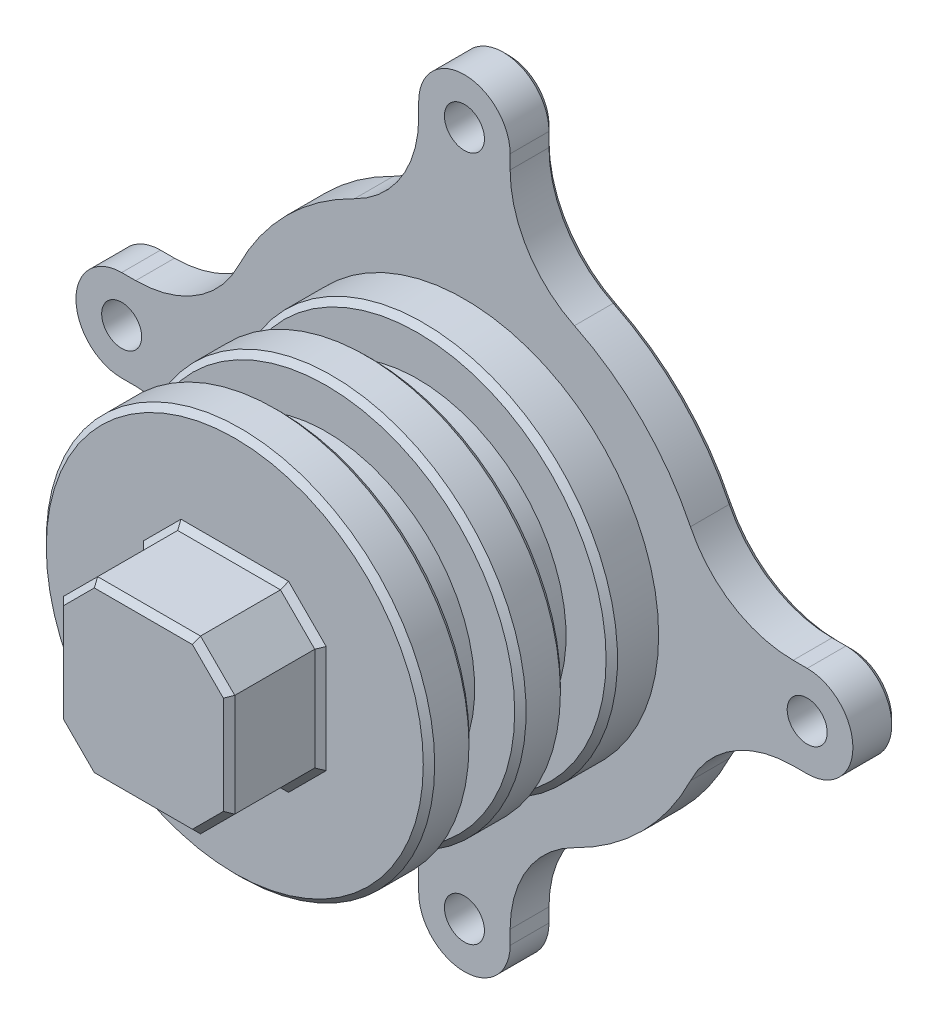
SolidWorks part; units mm, degrees
ref_plane "Front Plane" through (0, 0, 0) normal (0, 0, 1) x (1, 0, 0)
ref_plane "Top Plane" through (0, 0, 0) normal (0, 1, 0) x (1, 0, 0)
ref_plane "Right Plane" through (0, 0, 0) normal (1, 0, 0) x (0, 0, -1)
sketch "Sketch1" plane through (0, 0, 0) normal (0, 0, 1) x (1, 0, 0)
  circle A0 centre (0, 0) radius 25
  dimension "D1" = 50
ref_plane "Plane1" through (0, 0, 20) normal (0, 0, 1) x (1, 0, 0)
sketch "Sketch2" plane through (0, 0, 20) normal (0, 0, 1) x (1, 0, 0)
  circle A0 centre (0, 0) radius 15
  dimension "D1" = 30
loft "Loft1" add profiles "Sketch2", "Sketch1"
sketch "Sketch3" plane through (0, 0, 20) normal (0, 0, 1) x (1, 0, 0)
  circle A0 centre (0, 0) radius 15
  circle A1 centre (0, 0) radius 15 construction
extrude "Boss-Extrude1" add sketch "Sketch3" along normal blind 5
fillet "Fillet1" radius 10 1 edges at (15, 0, 20)
sketch "Sketch4" plane through (0, 0, 0) normal (0, 0, -1) x (-1, 0, 0)
  line L0 (0, 20) -> (0, -20) construction
  line L1 (-20, 0) -> (20, 0) construction
  circle A0 centre (0, 0) radius 20 construction
  circle A1 centre (0, 20) radius 1.75
  circle A2 centre (-20, 0) radius 1.75
  circle A3 centre (0, -20) radius 1.75
  circle A4 centre (20, 0) radius 1.75
  dimension "D1" = 40
  dimension "D2" = 3.5
  dimension "D3" = 3.5
  dimension "D4" = 3.5
  dimension "D5" = 3.5
extrude "Cut-Extrude1" cut sketch "Sketch4" against normal blind 130
ref_plane "Plane2" through (0, 0, 3) normal (0, 0, -1) x (-1, 0, 0)
sketch "Sketch5" plane through (0, 0, 3) normal (0, 0, -1) x (-1, 0, 0)
  circle A0 centre (0, 20) radius 4
  circle A1 centre (20, 0) radius 4
  circle A3 centre (-20, 0) radius 4
  circle A5 centre (0, -20) radius 4
  dimension "D1" = 8
  dimension "D2" = 8
  dimension "D3" = 8
  dimension "D4" = 8
extrude "Cut-Extrude2" cut sketch "Sketch5" against normal blind 130
sketch "Sketch6" plane through (0, 0, 25) normal (0, 0, 1) x (1, 0, 0)
  circle A0 centre (0, 0) radius 22
  dimension "D1" = 44
extrude "Boss-Extrude2" add sketch "Sketch6" along normal blind 4
sketch "Sketch7" plane through (0, 0, 29) normal (0, 0, 1) x (1, 0, 0)
  circle A0 centre (0, 0) radius 17
  circle A1 centre (0, 0) radius 22 construction
  dimension "D1" = 5
extrude "Boss-Extrude3" add sketch "Sketch7" along normal blind 20
sketch "Sketch8" [suppressed] plane through (0, 0, 0) normal (0, 1, 0) x (1, 0, 0)
  line L0 (0, -48) -> (0, -27)
  line L1 (-17, -48) -> (17, -48) construction
  line L3 (17, -48) -> (17, -28) construction
  line L4 (3, -24) -> (45.4819, -24)
  arc A0 (0, -27) -> (3, -24) centre (3, -27) cw
  point P9 (0, -24)
  dimension "D2" = 3
  dimension "D1" = 24
  dimension "D3" = 17
ref_plane "Plane5" through (14, 0, 0) normal (1, 0, 0) x (0, 0, -1)
sketch "Sketch14" [suppressed] plane through (14, 0, 0) normal (1, 0, 0) x (0, 0, -1)
  line L0 (-28, 20) -> (-28, -20) construction
  circle A0 centre (-24, 0) radius 4
  dimension "D1" = 8
sketch "Sketch9" [suppressed] plane through (0, 0, 48) normal (0, 0, 1) x (1, 0, 0)
  circle A0 centre (0, 0) radius 2.1
  dimension "D1" = 4.2
ref_plane "Plane4" through (14, 0, 0) normal (1, 0, 0) x (0, 0, -1)
sketch "Sketch10" plane through (0, 0, 49) normal (0, 0, 1) x (1, 0, 0)
  circle A0 centre (0, 0) radius 10
  circle A1 centre (0, 0) radius 17 construction
  dimension "D1" = 7
sketch "Sketch13" [suppressed] plane through (0, 0, 0) normal (0, 1, 0) x (1, 0, 0)
  line L0 (17, -28) -> (17, -48) construction
  line L1 (-20, -28) -> (20, -28) construction
  line L2 (17, -31.3668) -> (17, -44.6332)
  line L3 (0, -28) -> (0, -48) construction
  line L4 (-17, -28) -> (17, -28) construction
  line L5 (-17, -48) -> (17, -48) construction
  arc A0 (17, -31.3668) -> (17, -44.6332) centre (38.5, -38) ccw
  dimension "D1" = 45
  dimension "D2" = 21.5
  dimension "D3" = 10
ref_plane "Plane14" through (0, 0, 39) normal (0, 0, 1) x (1, 0, 0)
sketch "Sketch15" plane through (0, 0, 0) normal (0, 1, 0) x (1, 0, 0)
  line L0 (-17, -29) -> (-17, -49) construction
  line L1 (-21.4316, -33) -> (-13, -33)
  line L2 (-21.4316, -33) -> (-21.4316, -37)
  line L3 (-21.4316, -37) -> (-13, -37)
  line L4 (-13, -33) -> (-13, -37)
  line L5 (-21.5787, -41) -> (-13, -41)
  line L6 (-21.5787, -41) -> (-21.5787, -45)
  line L7 (-21.5787, -45) -> (-13, -45)
  line L8 (-13, -41) -> (-13, -45)
  line L9 (-17, -29) -> (17, -29) construction
  line L10 (0, -29) -> (0, -49) construction
  line L11 (-17, -49) -> (17, -49) construction
  dimension "D1" = 4
  dimension "D2" = 4
  dimension "D3" = 4
  dimension "D4" = 4
  dimension "D5" = 4
  dimension "D6" = 4
revolve "Cut-Revolve1" cut sketch "Sketch15" angle 360 about L10
sketch "Sketch18" plane through (0, 0, 0) normal (0, 0, -1) x (-1, 0, 0)
  circle A0 centre (0, 0) radius 12.5
  dimension "D1" = 25
extrude "Cut-Extrude5" cut sketch "Sketch18" against normal blind 20
sketch "Sketch19" plane through (0, 0, 25) normal (0, 0, -1) x (-1, 0, 0)
  circle A0 centre (0, 0) radius 47.9872
extrude "Cut-Extrude6" cut sketch "Sketch19" along normal through all
sketch "Sketch20" plane through (0, 0, 25) normal (0, 0, -1) x (-1, 0, 0)
  line L0 (-4, 30) -> (-4, 21.6333)
  line L1 (4, 30) -> (4, 21.6333)
  arc A0 (4, 30) -> (-4, 30) centre (0, 30) ccw
  circle A1 centre (0, 30) radius 1.75
  arc A2 (4, 21.6333) -> (-4, 21.6333) centre (0, 0) ccw
  dimension "D1" = 8
  dimension "D2" = 3.5
  dimension "D3" = 44
  dimension "D4" = 30
extrude "Boss-Extrude5" add sketch "Sketch20" against normal blind 4
pattern_circular "CirPattern3" count 4 over 360 about axis through (0, 0, 0) along (0, 0, 1) of "Boss-Extrude5"
fillet "Fillet2" radius 10 8 edges at (21.6333, 4, 27) (21.6333, -4, 27) (4, -21.6333, 27) (-4, -21.6333, 27) (-21.6333, -4, 27) (-21.6333, 4, 27) (-4, 21.6333, 27) (4, 21.6333, 27)
sketch "Sketch21" plane through (0, 0, 29) normal (0, 0, 1) x (1, 0, 0)
  circle A0 centre (0, 0) radius 20
  circle A1 centre (0, 0) radius 17 construction
  circle A2 centre (0, 0) radius 26
  dimension "D1" = 3
  dimension "D2" = 6
chamfer "Chamfer1" distance 0.5 angle 45 5 edges at (-17, 0, 33) (-17, 0, 41) (17, 0, 37) (17, 0, 49) (17, 0, 45)
sketch "Sketch22" plane through (0, 0, 0) normal (0, 1, 0) x (1, 0, 0)
  line L0 (0, -49) -> (0, -60.7563) construction
  line L1 (7.5, -57) -> (-7.5, -57)
  line L2 (7.5, -57) -> (7.5, -49)
  line L3 (7.5, -49) -> (-7.5, -49)
  line L4 (-7.5, -57) -> (-7.5, -49)
  line L5 (-16.5, -49) -> (16.5, -49) construction
  dimension "D1" = 15
  dimension "D2" = 8
  dimension "D3" = 7.5
extrude "Boss-Extrude6" add sketch "Sketch22" along normal mid plane 15
sketch "Sketch23" plane through (0, 0, 0) normal (0, 1, 0) x (1, 0, 0)
  line L0 (0, -57) -> (0, -66) construction
  line L1 (-7.5, -57) -> (7.5, -57) construction
  line L2 (7.5, -57) -> (7.5, -49) construction
  line L3 (7.5, -53.0096) -> (7.5, -49)
  line L4 (-7.5, -49) -> (-7.5, -57) construction
  line L5 (-7.5, -49) -> (-7.5, -53.0096)
  line L6 (-7.5, -49) -> (7.5, -49)
  arc A0 (7.5, -53.0096) -> (-7.5, -53.0096) centre (0, -66) ccw
  dimension "D2" = 30
  dimension "D1" = 9
chamfer "Chamfer2" distance 3 angle 45 4 edges at (7.5, -7.5, 53) (7.5, 7.5, 53) (-7.5, -7.5, 53) (-7.5, 7.5, 53)
chamfer "Chamfer3" distance 0.5 angle 45 16 edges at (-6, -6, 57) (-7.5, 0, 57) (-6, 6, 57) (0, 7.5, 57) (6, 6, 57) (7.5, 0, 57) (6, -6, 57) (0, -7.5, 57) (7.5, 0, 49) (6, 6, 49) (0, 7.5, 49) (-6, 6, 49) (-7.5, 0, 49) (6, -6, 49) (-6, -6, 49) (0, -7.5, 49)
sketch "Sketch24" plane through (0, 0, 29) normal (0, 0, 1) x (1, 0, 0)
  circle A0 centre (0, 0) radius 41.0173
  circle A1 centre (0, 0) radius 17 construction
  circle A2 centre (0, 0) radius 17
extrude "Cut-Extrude8" cut sketch "Sketch24" against normal blind 0.1
chamfer "Chamfer4" distance 0.5 angle 45 28 edges at (0, 34, 25) (4, 29.3875, 25) (-1.75, 30, 25) (-34, 0, 25) (-29.3875, 4, 25) (-30, -1.75, 25) (0, -34, 25) (-4, -29.3875, 25) (1.75, -30, 25) (34, 0, 25) (29.3875, -4, 25) (30, 1.75, 25) (15.5563, 15.5563, 25) (29.3875, 4, 25) (15.5563, -15.5563, 25) (4, -29.3875, 25) (-15.5563, -15.5563, 25) (-29.3875, -4, 25) (-15.5563, 15.5563, 25) (-4, 29.3875, 25) (23.4717, 5.5221, 25) (23.4717, -5.5221, 25) (5.5221, -23.4717, 25) (-5.5221, -23.4717, 25) (-23.4717, -5.5221, 25) (-23.4717, 5.5221, 25) (-5.5221, 23.4717, 25) (5.5221, 23.4717, 25)
